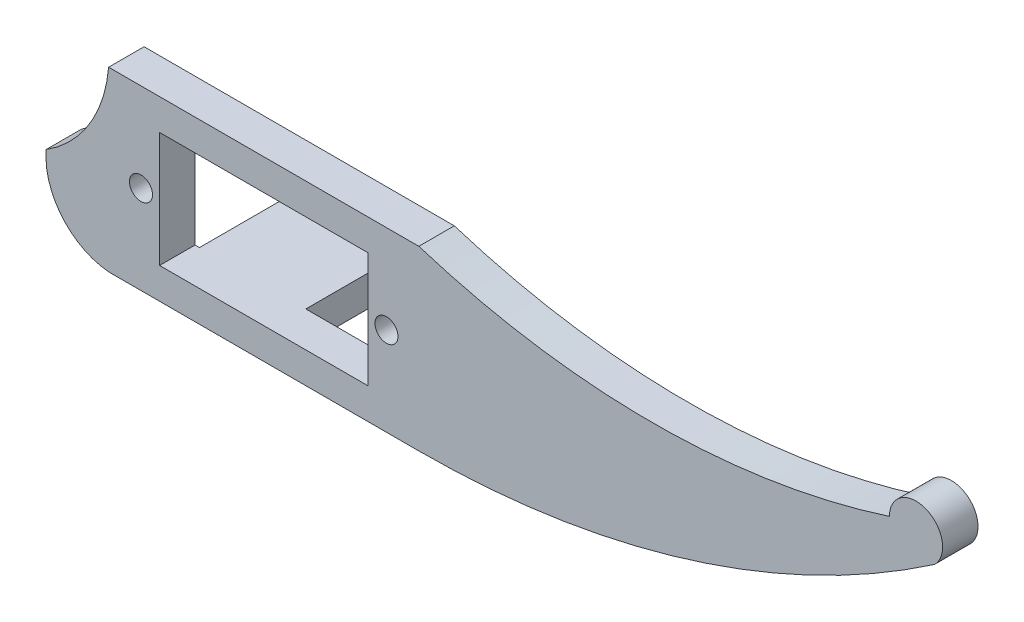
SolidWorks part; units mm, degrees
ref_plane "Front Plane" through (0, 0, 0) normal (0, 0, 1) x (1, 0, 0)
ref_plane "Top Plane" through (0, 0, 0) normal (0, 1, 0) x (1, 0, 0)
ref_plane "Right Plane" through (0, 0, 0) normal (1, 0, 0) x (0, 0, -1)
sketch "Sketch1" plane through (0, 0, 0) normal (0, 0, 1) x (1, 0, 0)
  line L1 (-4.3895, 3.8624) -> (19.1105, 3.8624)
  line L2 (-4.3895, 3.8624) -> (-4.3895, -9.1376)
  line L3 (-4.3895, -9.1376) -> (19.1105, -9.1376)
  line L4 (19.1105, 3.8624) -> (19.1105, -9.1376)
  line L5 (-10.1395, 7.3624) -> (24.8605, 7.3624)
  line L7 (-10.1395, -12.6376) -> (24.8605, -12.6376)
  arc A2 (-10.1395, 7.3624) -> (-17.1782, -4.1968) centre (-25.2144, 8.6193) cw
  arc A3 (-10.1395, -12.6376) -> (-17.1782, -4.1968) centre (-9.4384, -4.8979) cw
  arc A6 (82.1922, 4.7858) -> (77.9569, 7.5197) centre (80.9569, 7.5197) ccw
  arc A7 (24.8605, 7.3624) -> (77.9569, 7.5197) centre (51.1625, 90.5599) ccw
  arc A8 (24.8605, -12.6376) -> (83.036, 5.3569) centre (24.8605, 90.3991) ccw
  dimension "D1" = 23.5
  dimension "D2" = 13
  dimension "D3" = 3.5
  dimension "D4" = 3.5
extrude "Boss-Extrude1" add sketch "Sketch1" along normal blind 4 contours L7 A8 A6 A7 L5 A2 A3 L1 L4 L3 L2
sketch "Sketch3" plane through (0, 0, 4) normal (0, 0, 1) x (1, 0, 0)
  circle A0 centre (21.2105, -2.6376) radius 1.3
  circle A1 centre (-6.4895, -2.6376) radius 1.3
sketch "Sketch4" plane through (0, 0, 0) normal (0, 0, -1) x (-1, 0, 0)
  line L0 (4.3895, -9.1376) -> (-19.1105, -9.1376) construction
  line L1 (-8.1105, -9.1376) -> (3.8895, -9.1376)
  line L2 (-8.1105, -9.1376) -> (-8.1105, -12.6376)
  line L3 (-8.1105, -12.6376) -> (3.8895, -12.6376)
  line L4 (3.8895, -9.1376) -> (3.8895, -12.6376)
  line L5 (-8.1105, -9.1376) -> (-8.1105, -12.6376) construction
  line L6 (10.1395, -12.6376) -> (-24.8605, -12.6376) construction
  line L7 (3.8895, -12.6376) -> (3.8895, -9.1376) construction
extrude "Boss-Extrude3" add sketch "Sketch4" along normal blind 12
sketch "Sketch5" plane through (0, 0, -12) normal (0, 0, -1) x (-1, 0, 0)
  circle A0 centre (0.8895, -10.8876) radius 0.8
  circle A1 centre (-5.1105, -10.8876) radius 0.8
extrude "Cut-Extrude2" cut sketch "Sketch5" against normal blind 3
sketch "Sketch6" plane through (0, 0, 4) normal (0, 0, 1) x (1, 0, 0)
  circle A0 centre (21.2105, -2.6376) radius 1.3
  circle A1 centre (-6.4895, -2.6376) radius 1.3
extrude "Cut-Extrude3" cut sketch "Sketch6" against normal blind 4
